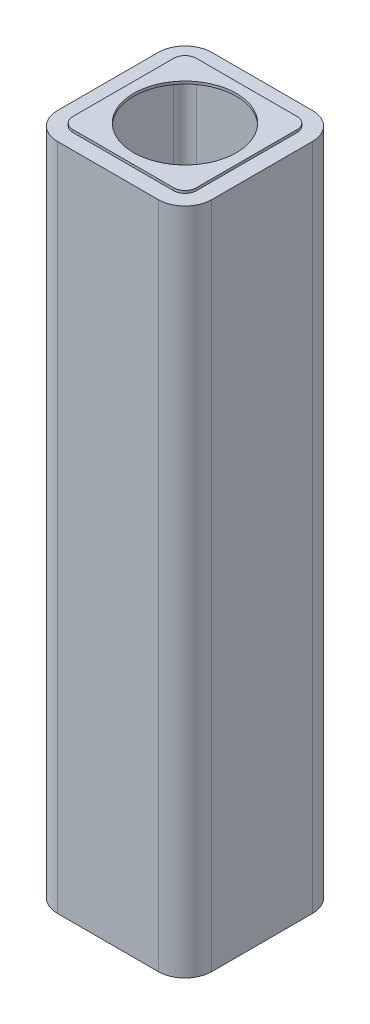
SolidWorks part; units mm, degrees
ref_plane "Front Plane" through (0, 0, 0) normal (0, 0, 1) x (1, 0, 0)
ref_plane "Top Plane" through (0, 0, 0) normal (0, 1, 0) x (1, 0, 0)
ref_plane "Right Plane" through (0, 0, 0) normal (1, 0, 0) x (0, 0, -1)
sketch3d "3DSketch1"
  line L0 (0, 0, 0) -> (0, 130, 0)
  dimension "D1" = 130
other "Square tube 30 X 30 X 2.6(1)"
ref_plane "Plane1" through (0, 0, 0) normal (0, 1, 0) x (1, 0, 0)
sketch "Sketch12" plane through (0, 0, 0) normal (0, 1, 0) x (1, 0, 0)
  line L0 (-9.8, -12) -> (9.8, -12)
  line L1 (-12, -9.8) -> (-12, 9.8)
  line L2 (9.8, 12) -> (-9.8, 12)
  line L3 (12, 9.8) -> (12, -9.8)
  line L4 (-9.8, -15) -> (9.8, -15)
  line L5 (-15, -9.8) -> (-15, 9.8)
  line L6 (9.8, 15) -> (-9.8, 15)
  line L7 (15, 9.8) -> (15, -9.8)
  arc A0 (15, 9.8) -> (9.8, 15) centre (9.8, 9.8) ccw
  arc A1 (9.8, -15) -> (15, -9.8) centre (9.8, -9.8) ccw
  arc A2 (-15, -9.8) -> (-9.8, -15) centre (-9.8, -9.8) ccw
  arc A3 (-9.8, 15) -> (-15, 9.8) centre (-9.8, 9.8) ccw
  arc A4 (-9.8, 12) -> (-12, 9.8) centre (-9.8, 9.8) ccw
  arc A5 (12, 9.8) -> (9.8, 12) centre (9.8, 9.8) ccw
  arc A6 (9.8, -12) -> (12, -9.8) centre (9.8, -9.8) ccw
  arc A7 (-12, -9.8) -> (-9.8, -12) centre (-9.8, -9.8) ccw
  point P0 (-15, 0)
  point P1 (15, 0)
  point P2 (0, 15)
  point P3 (0, -15)
  point P4 (0, 0)
  point P5 (-15, -15)
  point P6 (15, -15)
  point P7 (15, 15)
  point P8 (-15, 15)
  point P33 (0, 0)
  dimension "D1" = 5.2
  dimension "Thickness" = 3
  dimension "V_leg" = 30
sketch "Sketch13" plane through (0, 130, 0) normal (0, 1, 0) x (1, 0, 0)
  line L0 (12, -9.8) -> (12, 9.8) construction
  line L1 (-9.8, -12) -> (9.8, -12) construction
  line L2 (-12, 9.8) -> (-12, -9.8) construction
  line L3 (9.8, 12) -> (-9.8, 12) construction
  line L4 (12, -9.8) -> (12, 9.8)
  line L5 (-9.8, -12) -> (9.8, -12)
  line L6 (-12, 9.8) -> (-12, -9.8)
  line L7 (9.8, 12) -> (-9.8, 12)
  arc A0 (9.8, -12) -> (12, -9.8) centre (9.8, -9.8) ccw construction
  arc A1 (-12, -9.8) -> (-9.8, -12) centre (-9.8, -9.8) ccw construction
  arc A2 (-9.8, 12) -> (-12, 9.8) centre (-9.8, 9.8) ccw construction
  arc A3 (12, 9.8) -> (9.8, 12) centre (9.8, 9.8) ccw construction
  arc A4 (9.8, -12) -> (12, -9.8) centre (9.8, -9.8) ccw
  arc A5 (-12, -9.8) -> (-9.8, -12) centre (-9.8, -9.8) ccw
  arc A6 (-9.8, 12) -> (-12, 9.8) centre (-9.8, 9.8) ccw
  arc A7 (12, 9.8) -> (9.8, 12) centre (9.8, 9.8) ccw
  circle A8 centre (0, 0) radius 10
  dimension "D1" = 20
extrude "Boss-Extrude1" add sketch "Sketch13" along normal blind 0.5 separate body
